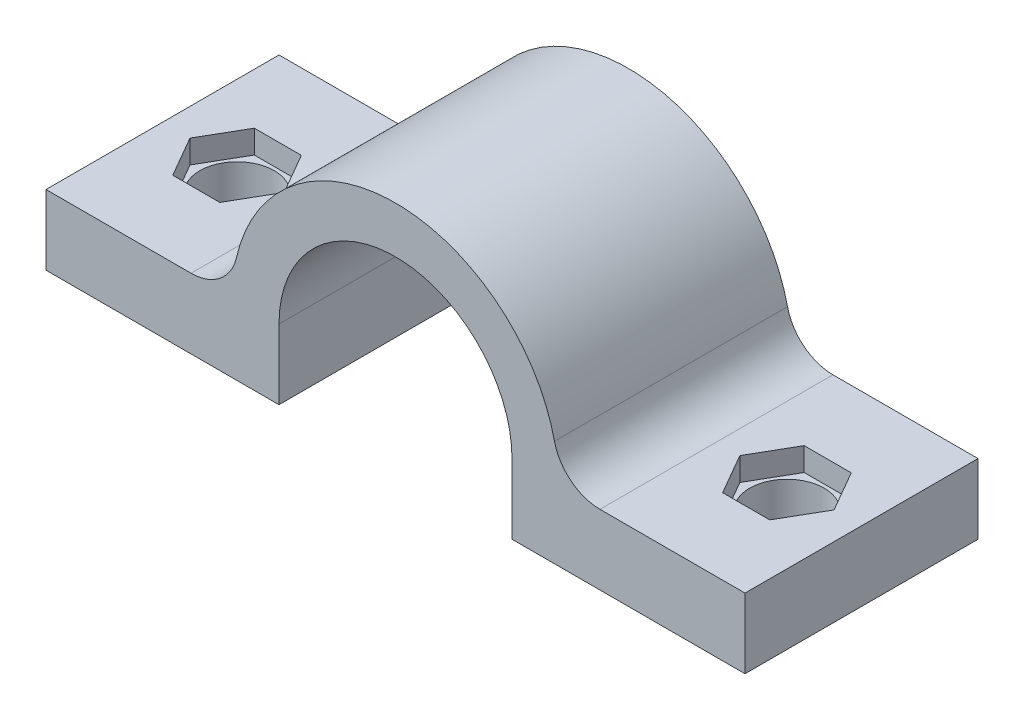
SolidWorks part; units mm, degrees
ref_plane "Front Plane" through (0, 0, 0) normal (0, 0, 1) x (1, 0, 0)
ref_plane "Top Plane" through (0, 0, 0) normal (0, 1, 0) x (1, 0, 0)
ref_plane "Right Plane" through (0, 0, 0) normal (1, 0, 0) x (0, 0, -1)
sketch "Sketch2" plane through (0, 0, 0) normal (0, 0, 1) x (1, 0, 0)
  line L0 (-5, 0) -> (5, 0) construction
  line L1 (-5, 0) -> (-15, 0)
  line L2 (5, 0) -> (15, 0)
  line L3 (-5, 0) -> (-7, 0)
  line L4 (5, 0) -> (7, 0)
  line L5 (-5, -3) -> (-15, -3)
  line L6 (-5, 0) -> (-5, -3)
  line L7 (-15, 0) -> (-15, -3)
  line L8 (5, -3) -> (15, -3)
  line L9 (5, 0) -> (5, -3)
  line L10 (15, 0) -> (15, -3)
  arc A1 (-5, 0) -> (5, 0) centre (0, 0) cw
  arc A2 (-7, 0) -> (7, 0) centre (0, 0) cw
  dimension "D4" = 5
  dimension "D1" = 180
  dimension "D2" = 10
  dimension "D3" = 2
  dimension "D5" = 3
  dimension "D6" = 3
extrude "Boss-Extrude1" add sketch "Sketch2" along normal blind 10 contours L1 L7 L5 L6 | A2 L1 A1 L2 | L10 L2 L9 L8
fillet "Fillet1" radius 2 2 edges at (7, 0, 5) (-7, 0, 5)
sketch "Sketch3" plane through (0, 0, 0) normal (0, 1, 0) x (1, 0, 0)
  line L0 (0, 0) -> (0, -10) construction
  line L1 (-6.825, -10) -> (6.825, -10) construction
  line L2 (8.775, -10) -> (15, -10) construction
  line L3 (15, -10) -> (15, 0) construction
  circle A0 centre (11.8, -5) radius 1.6
  circle A1 centre (-11.8, -5) radius 1.6
  dimension "D3" = 3.2
  dimension "D1" = 5
  dimension "D2" = 3.2
extrude "Cut-Extrude1" cut sketch "Sketch3" against normal through all
sketch "Sketch4" plane through (0, 0, 0) normal (0, 1, 0) x (1, 0, 0)
  line L1 (10.7896, -6.75) -> (12.8104, -6.75)
  line L2 (12.8104, -6.75) -> (13.8207, -5)
  line L3 (13.8207, -5) -> (12.8104, -3.25)
  line L4 (12.8104, -3.25) -> (10.7896, -3.25)
  line L5 (10.7896, -3.25) -> (9.7793, -5)
  line L6 (9.7793, -5) -> (10.7896, -6.75)
  line L7 (-12.8104, -6.75) -> (-10.7896, -6.75)
  line L8 (-10.7896, -6.75) -> (-9.7793, -5)
  line L9 (-9.7793, -5) -> (-10.7896, -3.25)
  line L10 (-10.7896, -3.25) -> (-12.8104, -3.25)
  line L11 (-12.8104, -3.25) -> (-13.8207, -5)
  line L12 (-13.8207, -5) -> (-12.8104, -6.75)
  circle A0 centre (11.8, -5) radius 1.75 construction
  circle A1 centre (-11.8, -5) radius 1.75 construction
  dimension "D1" = 3.5
  dimension "D2" = 3.5
extrude "Cut-Extrude2" cut sketch "Sketch4" against normal blind 1
